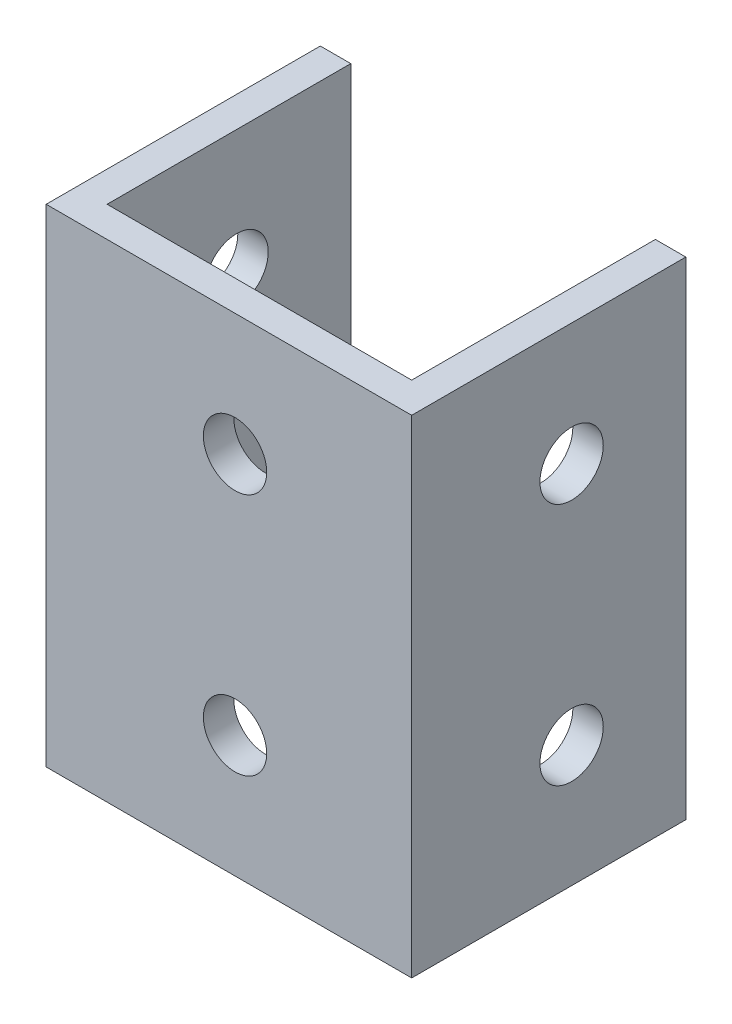
SolidWorks part; units mm, degrees
material "6061 Alloy"
ref_plane "Front Plane" through (0, 0, 0) normal (0, 0, 1) x (1, 0, 0)
ref_plane "Top Plane" through (0, 0, 0) normal (0, 1, 0) x (1, 0, 0)
ref_plane "Right Plane" through (0, 0, 0) normal (1, 0, 0) x (0, 0, -1)
sketch "Sketch2" plane through (0, 0, 0) normal (0, 1, 0) x (1, 0, 0)
  line L0 (0, 0) -> (0, -28.575)
  line L1 (0, -28.575) -> (38.1, -28.575)
  line L2 (38.1, -28.575) -> (38.1, 0)
  line L3 (38.1, 0) -> (34.925, 0)
  line L4 (34.925, 0) -> (34.925, -25.4)
  line L5 (34.925, -25.4) -> (3.175, -25.4)
  line L6 (3.175, -25.4) -> (3.175, 0)
  line L7 (3.175, 0) -> (0, 0)
  dimension "D1" = 28.575
  dimension "D2" = 38.1
  dimension "D3" = 3.175
  dimension "D4" = 3.175
  dimension "D5" = 3.175
extrude "Boss-Extrude1" add sketch "Sketch2" along normal blind 50.8
sketch "Sketch3" plane through (0, 0, 25.4) normal (0, 0, -1) x (-1, 0, 0)
  line L0 (-34.925, 0) -> (-3.175, 0) construction
  line L1 (-34.925, 50.8) -> (-34.925, 0) construction
  line L2 (-19.685, 0) -> (-19.685, 50.8) construction
  line L3 (-34.925, 50.8) -> (-3.175, 50.8) construction
  circle A0 centre (-19.685, 12.7) radius 3.302
  circle A1 centre (-19.685, 38.0911) radius 3.302
  dimension "D1" = 6.604
  dimension "D4" = 6.604
  dimension "D2" = 12.7
  dimension "D3" = 15.24
  dimension "D5" = 12.7089
  dimension "D6" = 15.24
extrude "Cut-Extrude1" cut sketch "Sketch3" against normal blind 50.8
sketch "Sketch4" plane through (38.1, 0, 0) normal (1, 0, 0) x (0, 0, -1)
  line L0 (-28.575, 50.8) -> (0, 50.8) construction
  line L3 (-28.575, 0) -> (0, 0) construction
  line L4 (0, 50.8) -> (0, 0) construction
  line L5 (0, 50.8) -> (0, 0) construction
  circle A0 centre (-11.9062, 38.1) radius 3.302
  circle A1 centre (-11.9062, 12.7) radius 3.302
  dimension "D1" = 6.604
  dimension "D2" = 12.7
  dimension "D3" = 12.7
  dimension "D4" = 11.9062
  dimension "D5" = 11.9062
extrude "Cut-Extrude2" cut sketch "Sketch4" against normal through all
